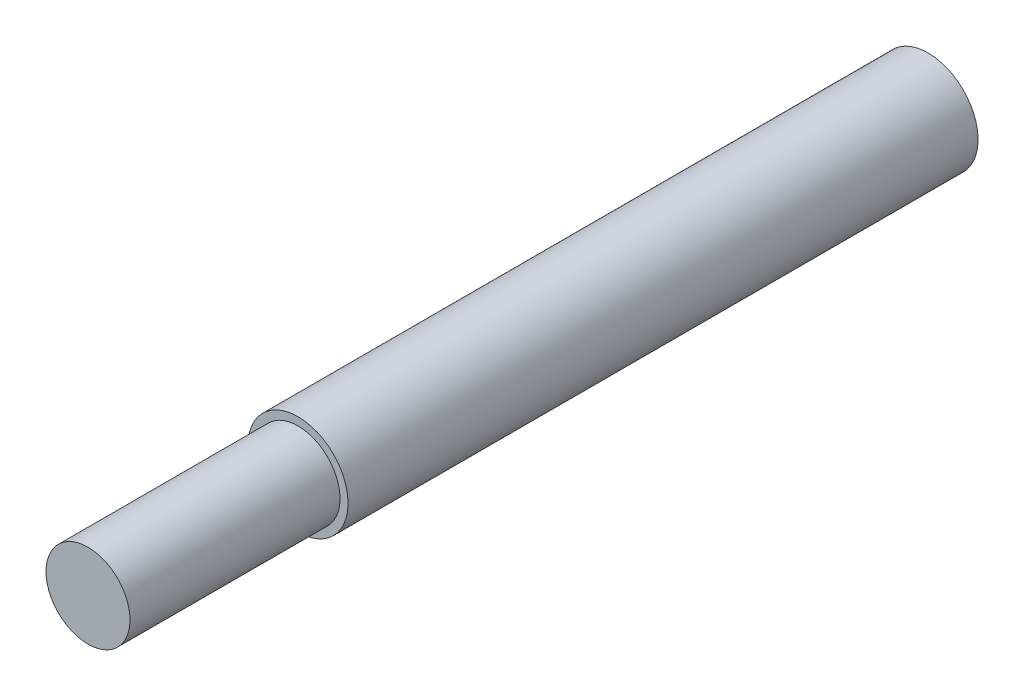
SolidWorks part; units mm, degrees
ref_plane "Plano frontal" through (0, 0, 0) normal (0, 0, 1) x (1, 0, 0)
ref_plane "Plano superior" through (0, 0, 0) normal (0, 1, 0) x (1, 0, 0)
ref_plane "Plano direito" through (0, 0, 0) normal (1, 0, 0) x (0, 0, -1)
sketch "Esboço1" plane through (0, 0, 0) normal (0, 0, 1) x (1, 0, 0)
  circle A0 centre (0, 0) radius 4
  dimension "D1" = 8
extrude "Ressalto-extrusão1" add sketch "Esboço1" along normal blind 20
sketch "Esboço2" plane through (0, 0, 0) normal (0, 0, -1) x (-1, 0, 0)
  circle A0 centre (0, 0) radius 4.7625
  dimension "D1" = 9.525
extrude "Ressalto-extrusão2" add sketch "Esboço2" along normal blind 60
